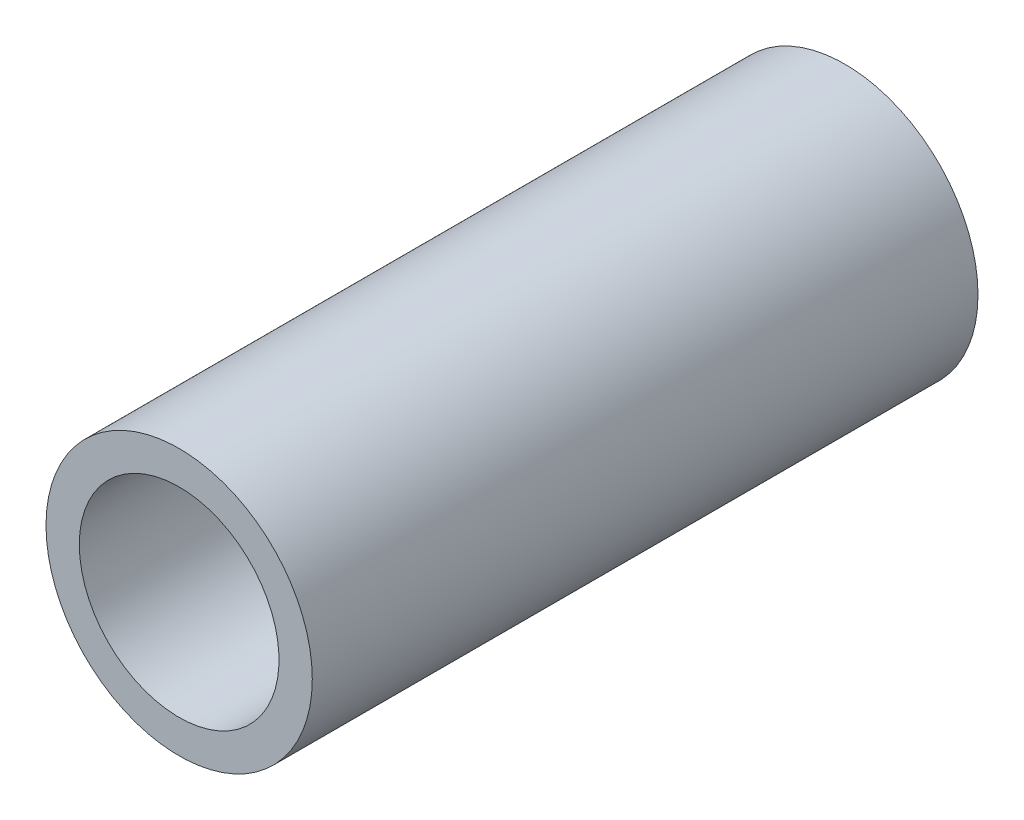
SolidWorks part; units mm, degrees
material "7075-O (SS)"
ref_plane "Front Plane" through (0, 0, 0) normal (0, 0, 1) x (1, 0, 0)
ref_plane "Top Plane" through (0, 0, 0) normal (0, 1, 0) x (1, 0, 0)
ref_plane "Right Plane" through (0, 0, 0) normal (1, 0, 0) x (0, 0, -1)
sketch "Sketch1" plane through (0, 0, 0) normal (0, 0, 1) x (1, 0, 0)
  circle A0 centre (0, 0) radius 12
  circle A1 centre (0, 0) radius 9
  dimension "D1" = 24
  dimension "D2" = 3
extrude "Boss-Extrude1" add sketch "Sketch1" along normal blind 60
